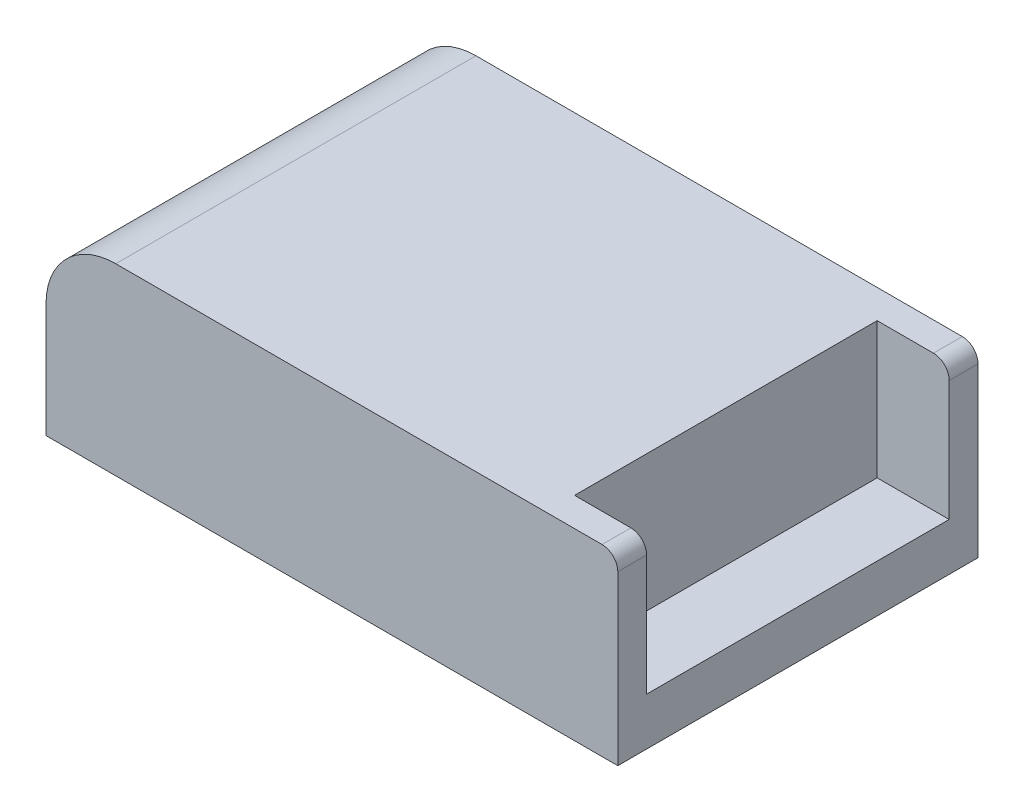
SolidWorks part; units mm, degrees
ref_plane "Front Plane" through (0, 0, 0) normal (0, 0, 1) x (1, 0, 0)
ref_plane "Top Plane" through (0, 0, 0) normal (0, 1, 0) x (1, 0, 0)
ref_plane "Right Plane" through (0, 0, 0) normal (1, 0, 0) x (0, 0, -1)
sketch "Sketch1" plane through (0, 0, 0) normal (0, 0, 1) x (1, 0, 0)
  line L2 (-91.3914, -26.617) -> (-141.7914, -26.617)
  line L3 (-141.7914, -26.617) -> (-141.7914, -16.5742)
  line L4 (-92.7789, -10.4242) -> (-135.6414, -10.4242)
  line L5 (-91.3914, -26.617) -> (-91.3914, -11.8117)
  line L6 (-92.7789, -10.4242) -> (-135.6414, -10.4242)
  line L7 (-91.3914, -26.617) -> (-91.3914, -11.8117)
  arc A6 (-138.1014, -10.9376) -> (-141.7914, -16.5742) centre (-135.6414, -16.5742) ccw
  arc A7 (-135.6414, -10.4242) -> (-138.1014, -10.9376) centre (-135.6414, -16.5742) ccw
  arc A8 (-91.3914, -11.8117) -> (-92.7789, -10.4242) centre (-92.7789, -11.8117) ccw
  arc A9 (-138.1014, -10.9376) -> (-141.7914, -16.5742) centre (-135.6414, -16.5742) ccw
  arc A10 (-135.6414, -10.4242) -> (-138.1014, -10.9376) centre (-135.6414, -16.5742) ccw
  arc A11 (-91.3914, -11.8117) -> (-92.7789, -10.4242) centre (-92.7789, -11.8117) ccw
  dimension "D1" = 0.2
extrude "Boss-Extrude1" add sketch "Sketch1" against normal up to surface (31.75 mm away)
sketch "ScrewHeadNotch" plane through (0, -10.4242, 0) normal (0, 1, 0) x (1, 0, 0)
  line L0 (-97.7414, 29.21) -> (-91.3914, 29.21)
  line L2 (-97.7414, 29.21) -> (-97.7414, 2.54)
  line L3 (-97.7414, 2.54) -> (-91.3914, 2.54)
  line L4 (-91.3914, 31.75) -> (-91.3914, 0) construction
  line L5 (-91.3914, 29.21) -> (-91.3914, 2.54)
  line L7 (-135.6414, 31.75) -> (-92.7789, 31.75) construction
  line L8 (-92.7789, 0) -> (-135.6414, 0) construction
  dimension "D1" = 2.54
  dimension "D2" = 2.54
  dimension "D3" = 6.35
extrude "Cut-Extrude1" cut sketch "ScrewHeadNotch" against normal blind 12
